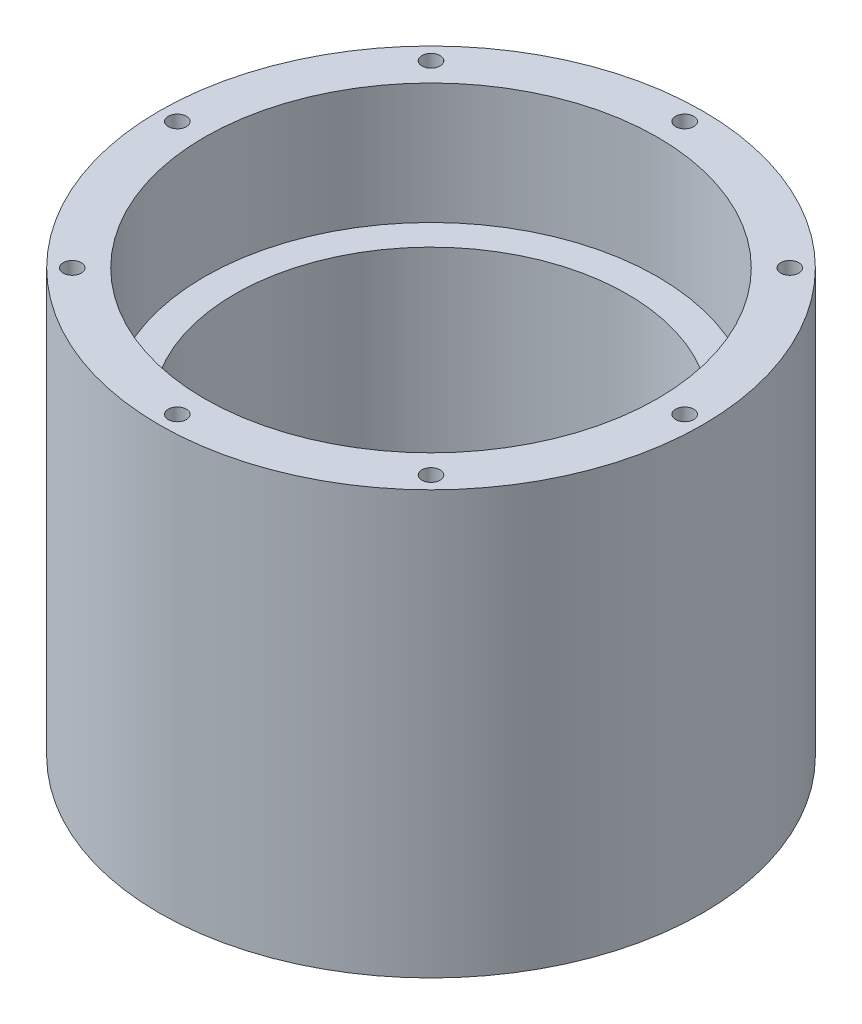
SolidWorks part; units mm, degrees
material "ASTM A36 Steel"
ref_plane "Front Plane" through (0, 0, 0) normal (0, 0, 1) x (1, 0, 0)
ref_plane "Top Plane" through (0, 0, 0) normal (0, 1, 0) x (1, 0, 0)
ref_plane "Right Plane" through (0, 0, 0) normal (1, 0, 0) x (0, 0, -1)
sketch "Sketch1" plane through (0, 0, 0) normal (0, 1, 0) x (1, 0, 0)
  circle A0 centre (0, 0) radius 45
  circle A1 centre (0, 0) radius 37.5
  dimension "D1" = 90
  dimension "D2" = 75
extrude "Boss-Extrude1" add sketch "Sketch1" along normal mid plane 70
sketch "Sketch2" plane through (0, 0, 0) normal (0, 1, 0) x (1, 0, 0)
  circle A0 centre (0, 0) radius 32.5
  dimension "D1" = 65
extrude "Extrude-Thin1" add sketch "Sketch2" along normal mid plane 30 thin
sketch "Sketch3" plane through (0, 35, 0) normal (0, 1, 0) x (1, 0, 0)
  circle A1 centre (0, 42) radius 1.5
  circle A2 centre (0, 0) radius 45 construction
  dimension "D1" = 3
  dimension "D2" = 42
extrude "Cut-Extrude1" cut sketch "Sketch3" against normal through all
pattern_circular "CirPattern1" count 8 over 360 about axis through (0, 0, 0) along (0, 1, 0) of "Cut-Extrude1"
